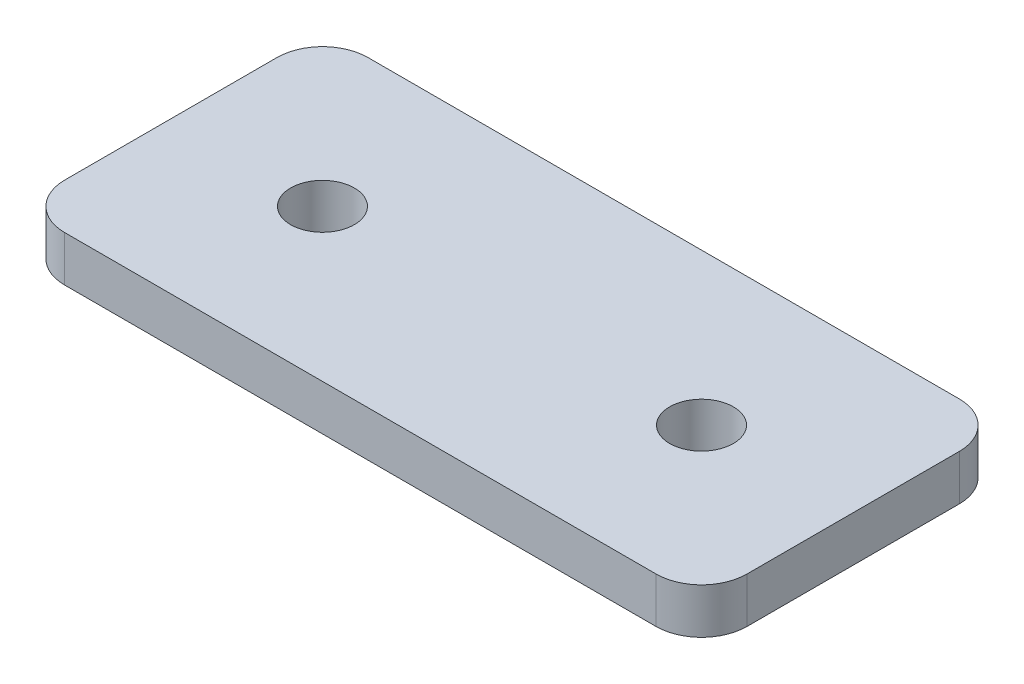
SolidWorks part; units mm, degrees
material "A-玻璃纤维"
ref_plane "前视基准面" through (0, 0, 0) normal (0, 0, 1) x (1, 0, 0)
ref_plane "上视基准面" through (0, 0, 0) normal (0, 1, 0) x (1, 0, 0)
ref_plane "右视基准面" through (0, 0, 0) normal (1, 0, 0) x (0, 0, -1)
sketch "草图1" plane through (0, 0, 0) normal (0, 1, 0) x (1, 0, 0)
  line L0 (0, 0) -> (25, 0) construction
  line L2 (-10, 10) -> (35, 10)
  line L3 (-10, 10) -> (-10, -10)
  line L4 (-10, -10) -> (35, -10)
  line L5 (35, 10) -> (35, -10)
  line L6 (-10, 10) -> (35, -10) construction
  line L7 (-10, -10) -> (35, 10) construction
  circle A0 centre (0, 0) radius 2.1
  circle A1 centre (25, 0) radius 2.1
  point P5 (12.5, 0)
  dimension "D1" = 25
  dimension "D2" = 4.2
  dimension "D4" = 10
  dimension "D3" = 20
extrude "凸台-拉伸1" add sketch "草图1" along normal blind 3
fillet "圆角1" radius 3 4 edges at (-10, 1.5, 10) (-10, 1.5, -10) (35, 1.5, -10) (35, 1.5, 10)
